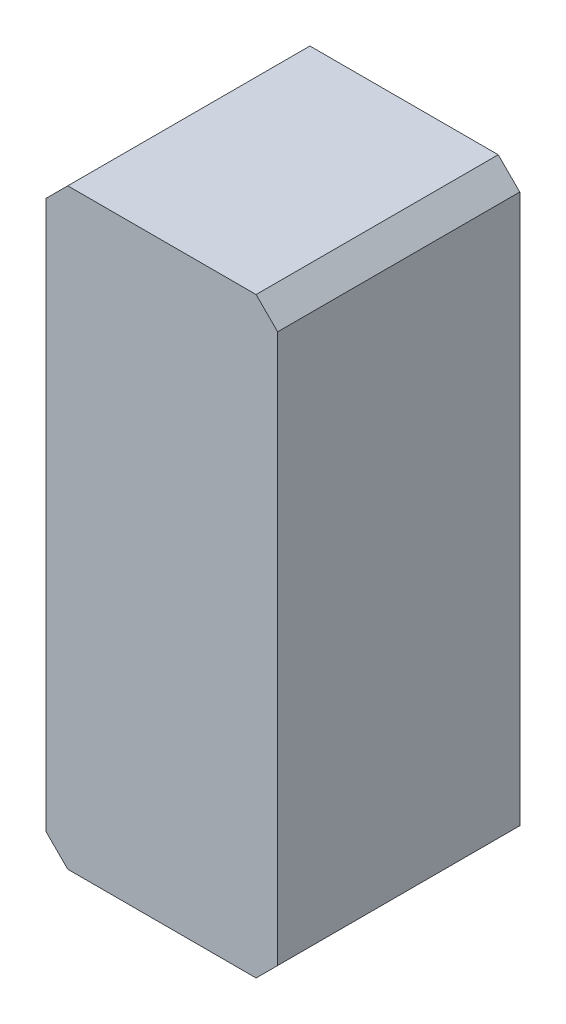
SolidWorks part; units mm, degrees
ref_plane "前视基准面" through (0, 0, 0) normal (0, 0, 1) x (1, 0, 0)
ref_plane "上视基准面" through (0, 0, 0) normal (0, 1, 0) x (1, 0, 0)
ref_plane "右视基准面" through (0, 0, 0) normal (1, 0, 0) x (0, 0, -1)
other "Configuration Table"
sketch "草图1" plane through (0, 0, 0) normal (0, 0, 1) x (1, 0, 0)
  line L8 (-17.5, -55) -> (17.5, -55)
  line L9 (17.5, -55) -> (21.5, -51)
  line L10 (21.5, -51) -> (21.5, 51)
  line L11 (21.5, 51) -> (17.5, 55)
  line L12 (17.5, 55) -> (-17.5, 55)
  line L13 (-17.5, 55) -> (-21.5, 51)
  line L14 (-21.5, 51) -> (-21.5, -51)
  line L15 (-21.5, -51) -> (-17.5, -55)
extrude "6S3000mAh临时外形" add sketch "草图1" along normal blind 45
